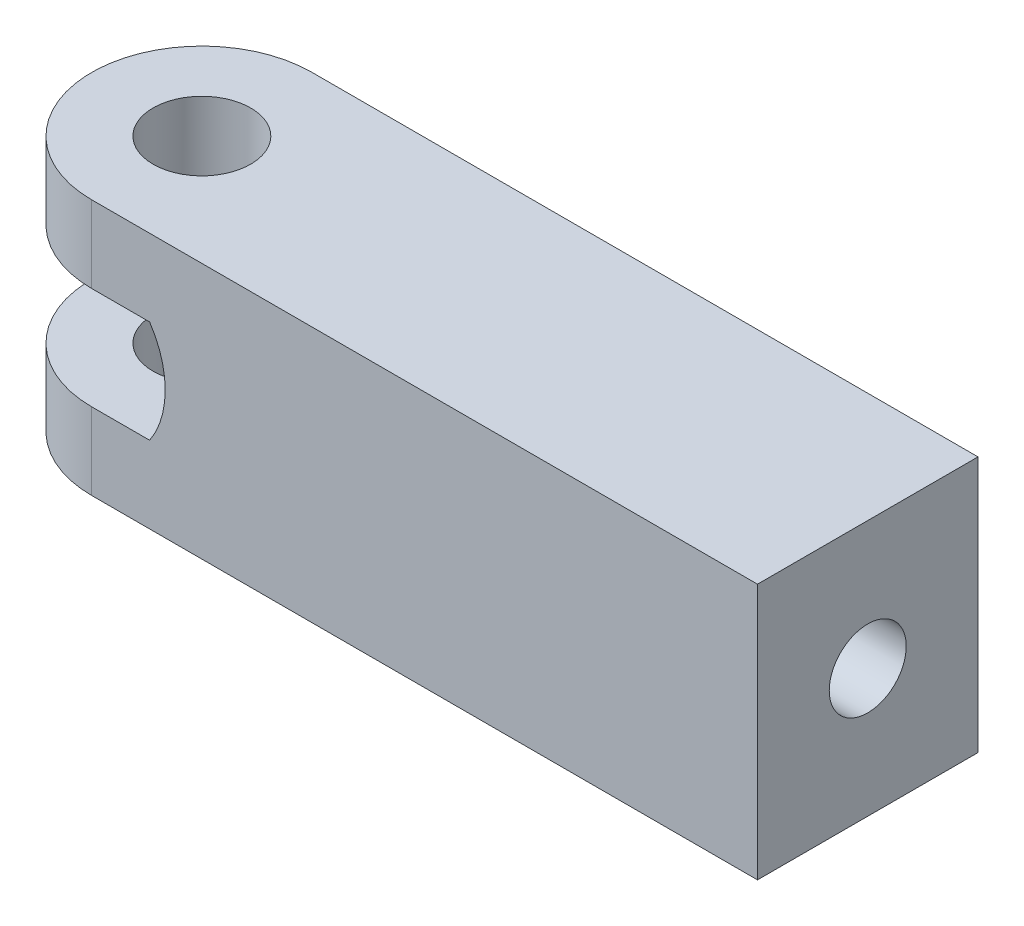
SolidWorks part; units mm, degrees
ref_plane "Front" through (0, 0, 0) normal (0, 0, 1) x (1, 0, 0)
ref_plane "Top" through (0, 0, 0) normal (0, 1, 0) x (1, 0, 0)
ref_plane "Right" through (0, 0, 0) normal (1, 0, 0) x (0, 0, -1)
sketch "Sketch2" plane through (0, 0, 0) normal (0, 1, 0) x (1, 0, 0)
  line L1 (-15, 15) -> (15, 15)
  line L2 (-15, 15) -> (-15, -15)
  line L3 (-15, -15) -> (15, -15)
  line L4 (15, 15) -> (15, -15)
  line L5 (-15, 15) -> (15, -15) construction
  line L6 (-15, -15) -> (15, 15) construction
  point P0 (0, 0)
  dimension "D1" = 30
  dimension "D2" = 30
extrude "Boss-Extrude3" add sketch "Sketch2" along normal mid plane 25
sketch "Sketch1" plane through (0, 0, 0) normal (0, 1, 0) x (1, 0, 0)
  line L0 (-10.7625, 0) -> (10, 0)
  line L1 (0, 10.7625) -> (15, 10.7625)
  line L2 (0, -10.7625) -> (15, -10.7625)
  line L3 (15, 10.7625) -> (15, -10.7625)
  line L5 (15, -15) -> (15, 15)
  line L6 (15, 15) -> (-15, 15)
  line L7 (-15, 15) -> (-15, -15)
  line L8 (-15, -15) -> (15, -15)
  line L9 (15, -15) -> (15, 15)
  line L10 (15, 15) -> (-15, 15)
  line L11 (-15, 15) -> (-15, -15)
  line L12 (-15, -15) -> (15, -15)
  circle A0 centre (0, 0) radius 4.7625
  arc A1 (0, 10.7625) -> (0, -10.7625) centre (0, 0) ccw
  dimension "D1" = 9.525
  dimension "D2" = 6
  dimension "D3" = 0
extrude "Cut-Extrude1" cut sketch "Sketch1" against normal through all both and the other way through all contours L12 L9 L10 L11 | A1 L2 L3 L1 | A0
sketch "Sketch3" plane through (0, 0, 10.7625) normal (0, 0, 1) x (1, 0, 0)
  line L0 (-10.7625, 12.5) -> (-10.7625, -12.5) construction
  line L1 (5.6651, -5) -> (-10.7625, -5)
  line L3 (5.6651, 5) -> (-10.7625, 5)
  line L4 (-10.7625, -5) -> (-10.7625, 5)
  line L5 (16.5, 0) -> (-16.5, 0) construction
  line L6 (15, -12.5) -> (15, 12.5) construction
  line L10 (-10.7625, 12.5) -> (15, 12.5)
  line L11 (-10.7625, 12.5) -> (-10.7625, -12.5)
  line L12 (-10.7625, -12.5) -> (15, -12.5)
  line L13 (15, 12.5) -> (15, -12.5)
  line L15 (-10.7625, 12.5) -> (15, 12.5)
  line L16 (-10.7625, 12.5) -> (-10.7625, -12.5)
  line L17 (-10.7625, -12.5) -> (15, -12.5)
  line L18 (15, 12.5) -> (15, -12.5)
  arc A0 (5.6651, 5) -> (5.6651, -5) centre (-1.7914, 0) cw
  point P0 (0, 0)
  point P8 (-10.7625, 0)
  point P23 (15, 0)
  line M5 (0, 12.5) -> (0, -12.5)
  dimension "D1" = 10
extrude "Cut-Extrude2" cut sketch "Sketch3" against normal through all both and the other way through all contours A0 L3 L1 M5 | L4 L1 L3 M5
sketch "Sketch5" plane through (15, 0, 0) normal (1, 0, 0) x (0, 0, -1)
  line L4 (10.7625, -12.5) -> (10.7625, 12.5)
  line L5 (-10.7625, -12.5) -> (10.7625, -12.5)
  line L6 (-10.7625, 12.5) -> (-10.7625, -12.5)
  line L7 (-10.7625, -12.5) -> (10.7625, -12.5)
  line L8 (10.7625, -12.5) -> (10.7625, 12.5)
  line L10 (-10.7625, 12.5) -> (-10.7625, -12.5)
  line L12 (10.7625, 12.5) -> (-10.7625, 12.5)
  line L13 (10.7625, 12.5) -> (-10.7625, 12.5)
  dimension "D1" = 0
extrude "Boss-Extrude4" add sketch "Sketch5" along normal blind 50
sketch "Sketch6" plane through (65, 0, 0) normal (1, 0, 0) x (0, 0, -1)
  circle A0 centre (0, 0) radius 3.7592
  dimension "D1" = 7.5184
fillet "Fillet2" [suppressed] radius 0.5
extrude "Cut-Extrude3" cut sketch "Sketch6" against normal blind 10 and the other way through all
